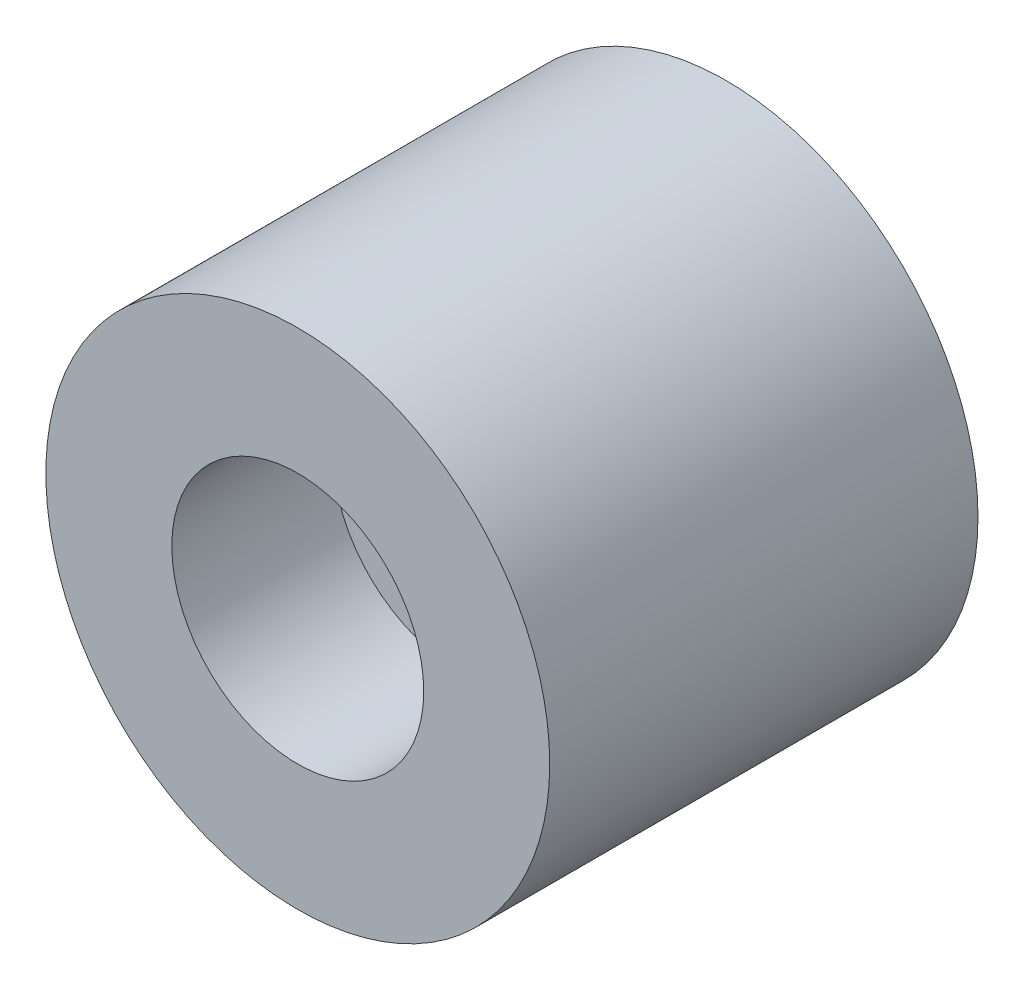
SolidWorks part; units mm, degrees
ref_plane "Front Plane" through (0, 0, 0) normal (0, 0, 1) x (1, 0, 0)
ref_plane "Top Plane" through (0, 0, 0) normal (0, 1, 0) x (1, 0, 0)
ref_plane "Right Plane" through (0, 0, 0) normal (1, 0, 0) x (0, 0, -1)
sketch "Sketch1" plane through (0, 0, 0) normal (0, 0, 1) x (1, 0, 0)
  line L2 (-0.4472, 1.3944) -> (-1.1359, 2.7719)
  line L3 (0.4472, 1.3944) -> (1.1359, 2.7719)
  line L5 (-0.4472, -1.3944) -> (-1.1359, -2.7719)
  line L6 (0.4472, -1.3944) -> (1.1359, -2.7719)
  arc A0 (-1.847, 2.973) -> (-1.847, -2.973) centre (0, 0) ccw
  arc A3 (1.847, -2.973) -> (1.847, 2.973) centre (0, 0) ccw
  arc A4 (0.4472, 1.3944) -> (-0.4472, 1.3944) centre (0, 1.618) cw
  arc A5 (0.4472, -1.3944) -> (-0.4472, -1.3944) centre (0, -1.618) ccw
  arc A6 (-1.1359, -2.7719) -> (-1.847, -2.973) centre (-1.5831, -2.5483) cw
  arc A7 (1.847, -2.973) -> (1.1359, -2.7719) centre (1.5831, -2.5483) cw
  arc A8 (1.847, 2.973) -> (1.1359, 2.7719) centre (1.5831, 2.5483) ccw
  arc A9 (-1.1359, 2.7719) -> (-1.847, 2.973) centre (-1.5831, 2.5483) ccw
  point P2 (0, 0)
  point P6 (0, 0)
  point P8 (0, 0)
  point P9 (3.5, 0)
  point P10 (-1.4471, 3.0294)
  point P11 (1.4471, 3.0294)
  point P12 (-1.4471, -3.0294)
  point P15 (1.4471, -3.0294)
  point P19 (0, 0)
  dimension "D1" = 7
  dimension "D2" = 0.5
  dimension "D3" = 0.5
  dimension "D4" = 0.5
  dimension "D5" = 0.5
  dimension "D6" = 0.5
  dimension "D7" = 0.5
  dimension "D8" = 2.8942
  dimension "D9" = 2.8942
  dimension "D10" = 1.3774
  dimension "D11" = 1.3774
  dimension "D12" = 1.3774
  dimension "D13" = 1.3774
sketch "Sketch2" plane through (0, 0, 0) normal (0, 0, 1) x (1, 0, 0)
  circle A0 centre (0, 0) radius 5
  dimension "D1" = 10
extrude "Boss-Extrude1" add sketch "Sketch2" along normal blind 8.5
extrude "Cut-Extrude1" cut sketch "Sketch1" along normal blind 5 contours L2 A9 A0 A6 L5 A5 L6 A7 A3 A8 L3 A4
sketch "Sketch3" plane through (0, 0, 8.5) normal (0, 0, 1) x (1, 0, 0)
  circle A0 centre (0, 0) radius 2.5
  dimension "D1" = 5
extrude "Cut-Extrude2" cut sketch "Sketch3" against normal blind 3.2 contours A0
sketch "Sketch5" plane through (0, 0, 5) normal (0, 0, -1) x (-1, 0, 0)
  circle A0 centre (0, 0) radius 0.35
  dimension "D1" = 0.7
extrude "Cut-Extrude4" cut sketch "Sketch5" against normal blind 1
